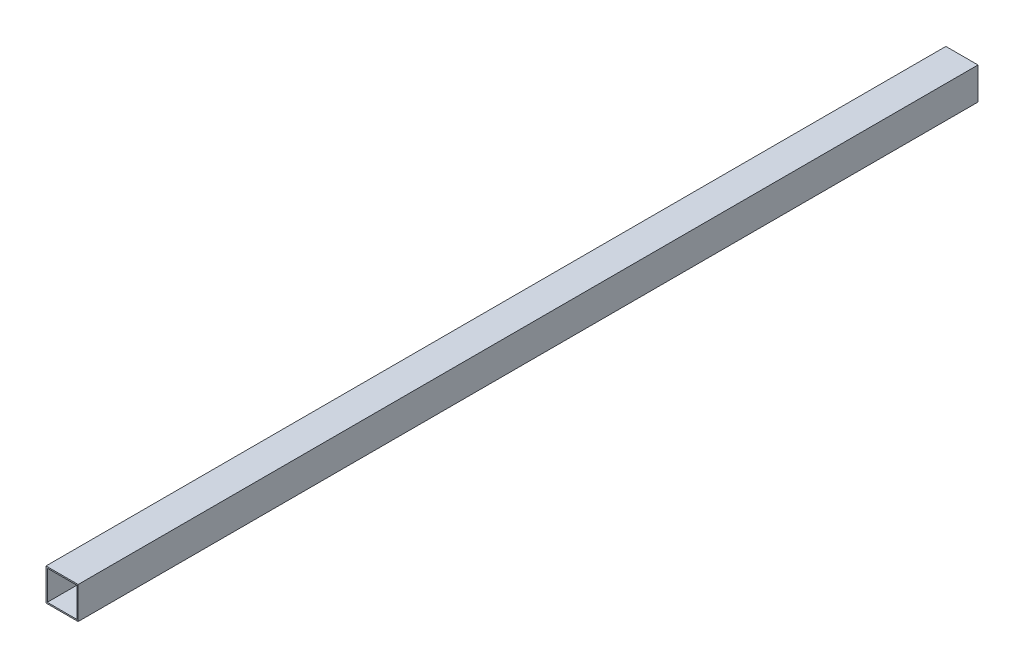
SolidWorks part; units mm, degrees
ref_plane "Front Plane" through (0, 0, 0) normal (0, 0, 1) x (1, 0, 0)
ref_plane "Top Plane" through (0, 0, 0) normal (0, 1, 0) x (1, 0, 0)
ref_plane "Right Plane" through (0, 0, 0) normal (1, 0, 0) x (0, 0, -1)
sketch "Sketch1" plane through (0, 0, 0) normal (0, 0, 1) x (1, 0, 0)
  line L0 (-13.8, 13.8) -> (13.8, 13.8)
  line L1 (-15, -15) -> (15, -15)
  line L2 (-15, -15) -> (-15, 15)
  line L3 (-15, 15) -> (15, 15)
  line L4 (15, -15) -> (15, 15)
  line L5 (-15, -15) -> (15, 15) construction
  line L6 (-15, 15) -> (15, -15) construction
  line L7 (13.8, -13.8) -> (13.8, 13.8)
  line L8 (-13.8, -13.8) -> (13.8, -13.8)
  line L9 (-13.8, -13.8) -> (-13.8, 13.8)
  point P0 (0, 0)
  dimension "D1" = 30
  dimension "D2" = 30
  dimension "D3" = 1.2
extrude "Boss-Extrude1" add sketch "Sketch1" along normal blind 840
